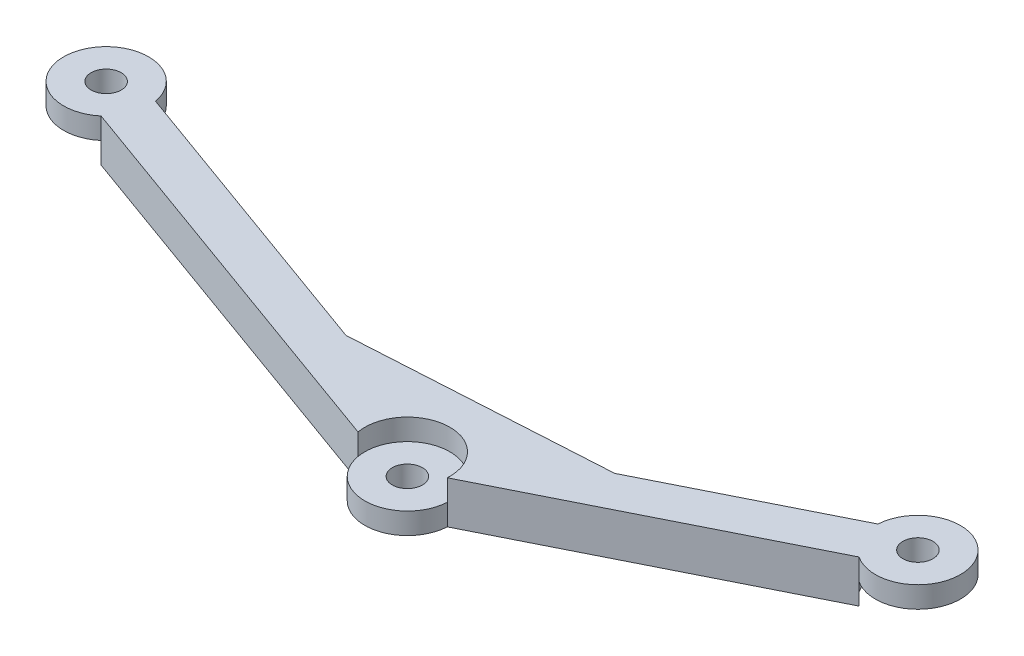
SolidWorks part; units mm, degrees
ref_plane "Front Plane" through (0, 0, 0) normal (0, 0, 1) x (1, 0, 0)
ref_plane "Top Plane" through (0, 0, 0) normal (0, 1, 0) x (1, 0, 0)
ref_plane "Right Plane" through (0, 0, 0) normal (1, 0, 0) x (0, 0, -1)
sketch "Sketch2" plane through (0, 0, 0) normal (0, 1, 0) x (1, 0, 0)
  line L0 (0, 0) -> (70.358, -25.4)
  line L1 (70.358, -25.4) -> (71.4361, -22.4136)
  line L2 (71.4361, -22.4136) -> (6.2506, 1.119)
  line L3 (69.2799, -28.3864) -> (4.0944, -4.8537)
  line L4 (70.358, -25.4) -> (121.158, 0)
  line L5 (121.158, 0) -> (119.7381, 2.8398)
  line L6 (119.7381, 2.8398) -> (73.8568, -20.1008)
  line L7 (122.5779, -2.8398) -> (76.6966, -25.7805)
  circle A0 centre (0, 0) radius 2.2479
  circle A1 centre (0, 0) radius 3.175
  circle A2 centre (0, 0) radius 6.35
  circle A9 centre (121.158, 0) radius 2.2479
  circle A10 centre (121.158, 0) radius 3.175
  circle A11 centre (121.158, 0) radius 6.35
  circle A12 centre (70.358, -25.4) radius 2.2479
  circle A13 centre (70.358, -25.4) radius 3.175
  circle A14 centre (70.358, -25.4) radius 6.35
  dimension "D1" = 4.4958
  dimension "D2" = 6.35
  dimension "D3" = 12.7
  dimension "D4" = 4.4958
  dimension "D5" = 6.35
  dimension "D6" = 12.7
  dimension "D7" = 4.4958
  dimension "D8" = 6.35
  dimension "D9" = 12.7
  dimension "D10" = 121.158
  dimension "D11" = 50.8
  dimension "D12" = 25.4
extrude "Boss-Extrude2" add sketch "Sketch2" along normal blind 6.35
sketch "Sketch3" plane through (0, 0, 0) normal (0, -1, 0) x (1, 0, 0)
  circle A0 centre (0, 0) radius 6.35
  circle A1 centre (121.158, 0) radius 6.35
extrude "Cut-Extrude1" cut sketch "Sketch3" against normal blind 3.175
sketch "Sketch4" plane through (0, 6.35, 0) normal (0, 1, 0) x (1, 0, 0)
  circle A0 centre (70.358, -25.4) radius 6.35
extrude "Cut-Extrude2" cut sketch "Sketch4" against normal blind 3.175
sketch "Sketch7" plane through (0, 0, 0) normal (0, -1, 0) x (1, 0, 0)
  line L0 (66.2636, 20.5463) -> (50.7345, 14.9402)
  line L1 (66.2636, 20.5463) -> (6.2506, -1.119) construction
  line L2 (73.8568, 20.1008) -> (88.6238, 12.7174)
  line L3 (114.8194, -0.3805) -> (73.8568, 20.1008) construction
  line L4 (88.6238, 12.7174) -> (50.7345, 14.9402)
  circle A1 centre (70.358, 25.4) radius 6.35
  line M7 (6.2506, -1.119) -> (66.2636, 20.5463)
  arc M8 (66.2636, 20.5463) -> (73.8568, 20.1008) centre (70.358, 25.4) ccw
  line M9 (73.8568, 20.1008) -> (114.8194, -0.3805)
  dimension "D1" = 16.51
  dimension "D2" = 16.51
extrude "Boss-Extrude4" add sketch "Sketch7" against normal blind 6.35 contours L4 M9 M8 M7
